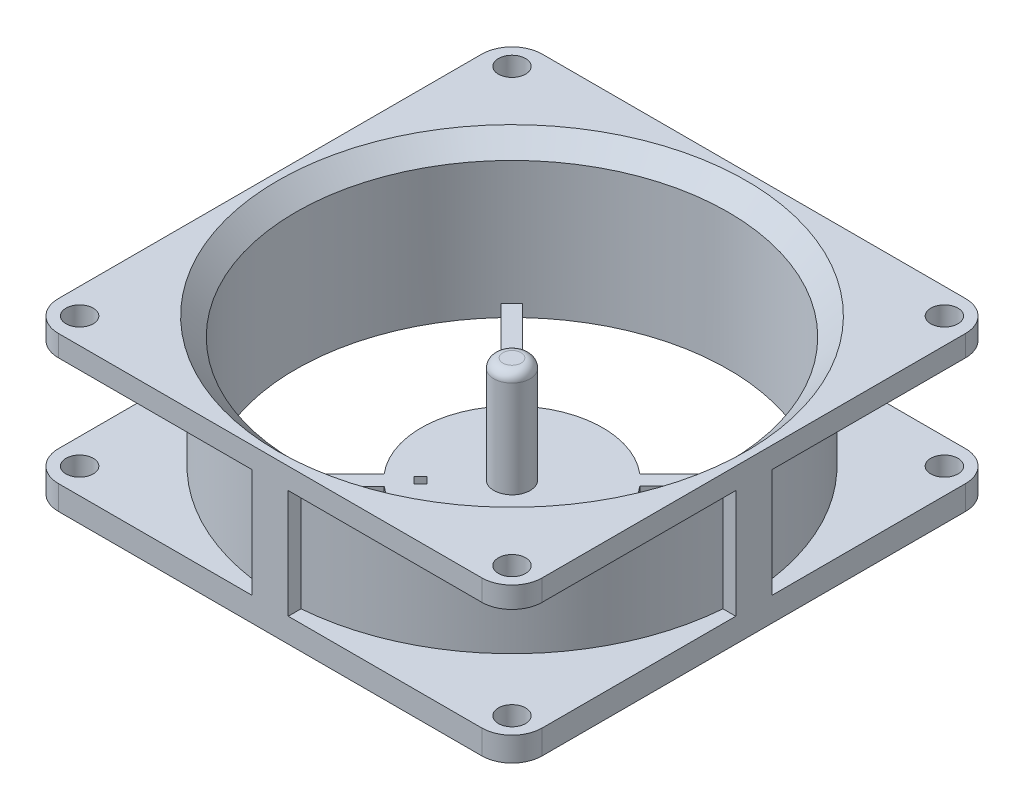
SolidWorks part; units mm, degrees
ref_plane "Front Plane" through (0, 0, 0) normal (0, 0, 1) x (1, 0, 0)
ref_plane "Top Plane" through (0, 0, 0) normal (0, 1, 0) x (1, 0, 0)
ref_plane "Right Plane" through (0, 0, 0) normal (1, 0, 0) x (0, 0, -1)
sketch "Sketch1" plane through (0, 0, 0) normal (0, 1, 0) x (1, 0, 0)
  line L1 (-40, 40) -> (40, 40)
  line L2 (-40, 40) -> (-40, -40)
  line L3 (-40, -40) -> (40, -40)
  line L4 (40, 40) -> (40, -40)
  dimension "D1" = 80
  dimension "D2" = 80
  dimension "D3" = 40
  dimension "D4" = 40
extrude "Boss-Extrude1" add sketch "Sketch1" along normal blind 25.5
sketch "Sketch2" plane through (0, 25.5, 0) normal (0, 1, 0) x (1, 0, 0)
  circle A0 centre (0, 0) radius 35.75
  dimension "D1" = 71.5
extrude "Cut-Extrude2" cut sketch "Sketch2" against normal blind 28
sketch "Sketch4" plane through (0, 0, 0) normal (0, -1, 0) x (1, 0, 0)
  line L0 (0, 0) -> (0, 35.75) construction
  line L1 (0, 0) -> (-35.75, 0) construction
  line L2 (-1.75, 0) -> (0, 1.7855)
  line L3 (-24.3705, 26.1561) -> (0, 1.7855)
  line L4 (-26.1389, 24.3889) -> (-1.75, 0)
  circle A0 centre (0, 0) radius 35.75 construction
  arc A1 (-24.3705, 26.1561) -> (-26.1389, 24.3889) centre (0, 0) ccw
  dimension "D1" = 2.5
  dimension "D2" = 1.75
  dimension "D3" = 45
extrude "Boss-Extrude2" add sketch "Sketch4" against normal blind 2
pattern_circular "CirPattern2" count 4 every 90 about axis through (0, 0, 0) along (0, 1, 0) of "Boss-Extrude2"
sketch "Sketch5" plane through (0, 0, 0) normal (0, -1, 0) x (1, 0, 0)
  circle A0 centre (0, 0) radius 15
  dimension "D1" = 30
extrude "Boss-Extrude3" add sketch "Sketch5" against normal blind 2
sketch "Sketch6" plane through (0, 2, 0) normal (0, 1, 0) x (1, 0, 0)
  circle A0 centre (0, 0) radius 3
extrude "Boss-Extrude4" add sketch "Sketch6" along normal blind 17.5
fillet "Fillet1" radius 1.5 1 edges at (0, 19.5, 3)
ref_plane "Plane1" through (0, 4, 0) normal (0, -1, 0) x (1, 0, 0)
sketch "Sketch7" plane through (0, 4, 0) normal (0, -1, 0) x (1, 0, 0)
  circle A0 centre (0, 0) radius 38
  circle A1 centre (0, 0) radius 70
  dimension "D1" = 76
extrude "Cut-Extrude4" cut sketch "Sketch7" against normal blind 18
fillet "Fillet2" radius 5 8 edges at (40, 2, -40) (40, 23.75, -40) (-40, 23.75, -40) (-40, 2, -40) (-40, 2, 40) (-40, 23.75, 40) (40, 23.75, 40) (40, 2, 40)
sketch "Sketch8" plane through (0, 4, 0) normal (0, -1, 0) x (1, 0, 0)
  line L0 (35, 40) -> (-35, 40) construction
  line L1 (-3, 40) -> (3, 40)
  line L2 (-3, 40) -> (-3, 35.6239)
  line L4 (3, 40) -> (3, 35.6239)
  circle A0 centre (0, 0) radius 35.75 construction
  arc A1 (-3, 35.6239) -> (3, 35.6239) centre (0, 0) cw
  dimension "D1" = 3
  dimension "D2" = 3
extrude "Boss-Extrude5" add sketch "Sketch8" against normal blind 20
pattern_circular "CirPattern3" count 4 every 90 about axis through (0, 0, 0) along (0, 1, 0) of "Boss-Extrude5"
sketch "Sketch9" plane through (0, 25.5, 0) normal (0, 1, 0) x (-1, 0, 0)
  circle A0 centre (35.75, -35.75) radius 2.25
  dimension "D3" = 4.5
  dimension "D1" = 35.75
  dimension "D2" = 35.75
extrude "Cut-Extrude5" cut sketch "Sketch9" against normal blind 37
pattern_linear "LPattern1" count 2 spacing 71.5 along (1, 0, 0) count 2 spacing 71.5 along (0, 0, 1) of "Cut-Extrude5"
chamfer "Chamfer2" distance 3 angle 45 1 edges at (0, 25.5, 35.75)
sketch "Sketch11" plane through (0, 0, 0) normal (0, -1, 0) x (1, 0, 0)
  line L0 (-28.8632, 27.8203) -> (-7.5549, 6.512)
  line L1 (-7.5549, 6.512) -> (-6.4942, 7.5726)
  line L2 (-6.4942, 7.5726) -> (-28.2419, 29.3203)
  line L3 (-28.8632, 27.8203) -> (-40, 27.8203)
  line L4 (-9.6762, 11.4617) -> (-24.3705, 26.1561) construction
  line L5 (-26.1389, 24.3889) -> (-11.4454, 9.6954) construction
  line L6 (-40, -35) -> (-40, 35) construction
  line L7 (-40, 27.8203) -> (-40, 29.3203)
  line L8 (-40, 29.3203) -> (-28.2419, 29.3203)
  dimension "D1" = 0.5
  dimension "D2" = 0.5
  dimension "D3" = 5
  dimension "D4" = 5
  dimension "D5" = 1.5
extrude "Cut-Extrude6" cut sketch "Sketch11" against normal blind 1
sketch "Sketch12" plane through (0, 1, 0) normal (0, -1, 0) x (1, 0, 0)
  line L0 (-6.4942, 7.5726) -> (-7.5549, 8.6333)
  line L1 (-6.4942, 7.5726) -> (-28.2419, 29.3203) construction
  line L2 (-7.5549, 8.6333) -> (-8.6155, 7.5726)
  line L3 (-28.8632, 27.8203) -> (-7.5549, 6.512) construction
  line L4 (-8.6155, 7.5726) -> (-7.5549, 6.512)
  line L5 (-7.5549, 6.512) -> (-6.4942, 7.5726)
  dimension "D1" = 1.5
extrude "Cut-Extrude7" cut sketch "Sketch12" against normal blind 7
scale "Scale1" scale about centroid uniform scaling yes scale factor 1.5
